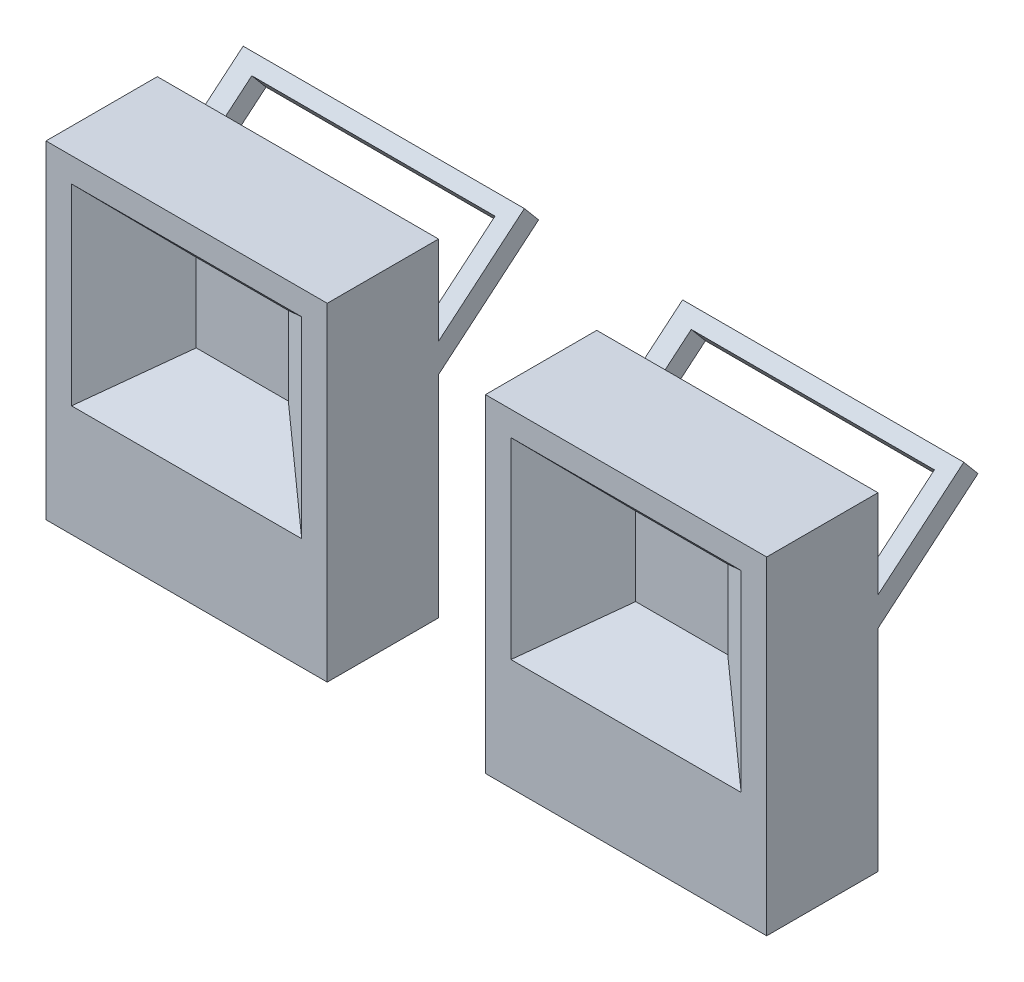
SolidWorks part; units mm, degrees
ref_plane "Front Plane" through (0, 0, 0) normal (0, 0, 1) x (1, 0, 0)
ref_plane "Top Plane" through (0, 0, 0) normal (0, 1, 0) x (1, 0, 0)
ref_plane "Right Plane" through (0, 0, 0) normal (1, 0, 0) x (0, 0, -1)
sketch "Sketch1" plane through (0, 0, 0) normal (0, 0, 1) x (1, 0, 0)
  line L1 (-48, 56) -> (48, 56)
  line L2 (-48, 56) -> (-48, -56)
  line L3 (-48, -56) -> (48, -56)
  line L4 (48, 56) -> (48, -56)
  line L5 (-48, 56) -> (48, -56) construction
  line L6 (-48, -56) -> (48, 56) construction
  point P0 (0, 0)
  dimension "D1" = 96
  dimension "D2" = 112
extrude "Boss-Extrude1" add sketch "Sketch1" along normal mid plane 38
sketch "Sketch2" plane through (0, 0, 0) normal (0, 0, 1) x (1, 0, 0)
  line L1 (-36.1246, 45.6133) -> (36.1246, 45.6133)
  line L2 (-36.1246, 45.6133) -> (-36.1246, -15.9274)
  line L3 (-36.1246, -15.9274) -> (36.1246, -15.9274)
  line L4 (36.1246, 45.6133) -> (36.1246, -15.9274)
  line L5 (-36.1246, 45.6133) -> (36.1246, -15.9274) construction
  line L6 (-36.1246, -15.9274) -> (36.1246, 45.6133) construction
  line L7 (-15.721, 28.2338) -> (15.721, 28.2338)
  line L8 (-15.721, 28.2338) -> (-15.721, 1.4521)
  line L9 (-15.721, 1.4521) -> (15.721, 1.4521)
  line L10 (15.721, 28.2338) -> (15.721, 1.4521)
  line L11 (-15.721, 28.2338) -> (15.721, 1.4521) construction
  line L12 (-15.721, 1.4521) -> (15.721, 28.2338) construction
  point P0 (0, 14.8429)
  point P5 (0, 14.8429)
sketch "Sketch3" plane through (0, 0, 19) normal (0, 0, 1) x (1, 0, 0)
  line L1 (-39.2835, 47.6465) -> (39.2835, 47.6465)
  line L2 (-39.2835, 47.6465) -> (-39.2835, -17.9606)
  line L3 (-39.2835, -17.9606) -> (39.2835, -17.9606)
  line L4 (39.2835, 47.6465) -> (39.2835, -17.9606)
  line L5 (-39.2835, 47.6465) -> (39.2835, -17.9606) construction
  line L6 (-39.2835, -17.9606) -> (39.2835, 47.6465) construction
  point P0 (0, 14.8429)
loft "Cut-Loft1" cut profiles "Sketch3" section "Sketch3" section "Sketch2"
sketch "Sketch5" plane through (-48, 0, 0) normal (-1, 0, 0) x (0, 0, 1)
  line L0 (0, 0) -> (-53.1413, 44.5909)
  line L2 (-48.2965, 50.3647) -> (0, 9.8392)
  line L3 (0, 9.8392) -> (0, 0)
  line L4 (-19, 56) -> (-19, -56) construction
  line L5 (-53.1413, 44.5909) -> (-48.2965, 50.3647)
  dimension "D1" = 50
extrude "Boss-Extrude2" add sketch "Sketch5" against normal up to surface (96 mm away) up to face at (48, 0, 0)
sketch "Sketch6" plane through (0, 0, 0) normal (0, -0.766, -0.6428) x (1, 0, 0)
  line L1 (-41.0879, -28.4401) -> (41.9146, -28.4401)
  line L2 (-41.0879, -28.4401) -> (-41.0879, -64.215)
  line L3 (-41.0879, -64.215) -> (41.9146, -64.215)
  line L4 (41.9146, -28.4401) -> (41.9146, -64.215)
extrude "Cut-Extrude1" cut sketch "Sketch6" against normal up to surface (7.5373 mm away) up to face at (0, 38.0734, -33.6482)
pattern_linear "LPattern1" count 2 spacing 150 along (1, 0, 0) of bodies 104
